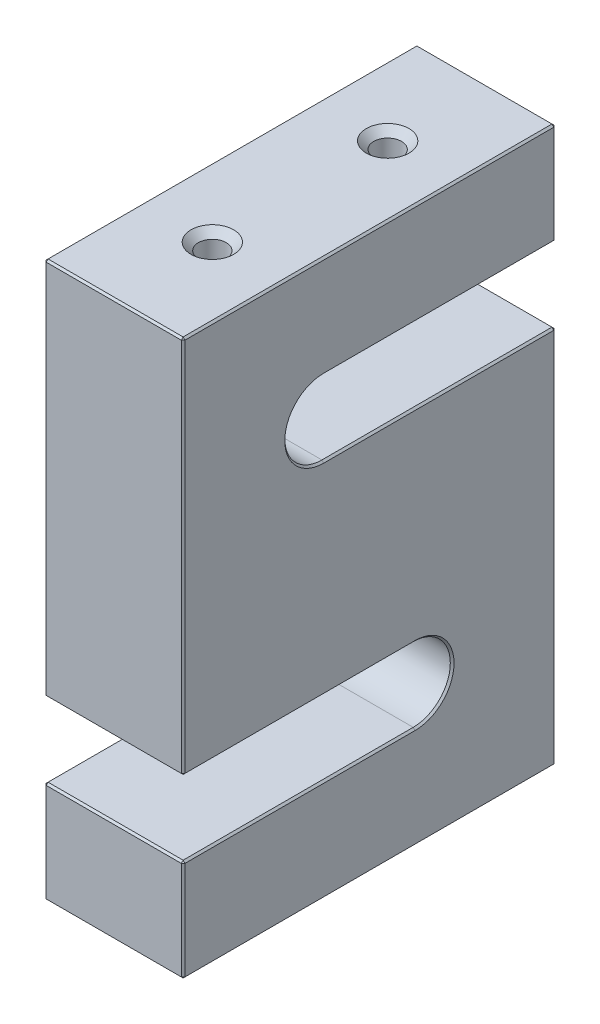
SolidWorks part; units mm, degrees
ref_plane "Front" through (0, 0, 0) normal (0, 0, 1) x (1, 0, 0)
ref_plane "Top" through (0, 0, 0) normal (0, 1, 0) x (1, 0, 0)
ref_plane "Right" through (0, 0, 0) normal (1, 0, 0) x (0, 0, -1)
sketch "Sketch1" plane through (0, 0, 0) normal (1, 0, 0) x (0, 0, -1)
  line L0 (-25.5, 0) -> (25.5, 0) construction
  line L1 (25.5, -38) -> (-25.5, -38) construction
  line L2 (25.5, -38) -> (25.5, 13.92)
  line L3 (25.5, 38) -> (-25.5, 38) construction
  line L4 (-25.5, -38) -> (-25.5, 38) construction
  line L5 (25.5, -38) -> (-25.5, 38) construction
  line L6 (25.5, 38) -> (-25.5, -38) construction
  line L7 (-25.5, 19) -> (25.5, 19) construction
  line L8 (-6.25, 19) -> (29.6244, 19) construction
  line L9 (-6.25, 24.08) -> (25.5, 24.08) construction
  line L10 (-6.25, 13.92) -> (25.5, 13.92) construction
  line L11 (6.25, -24.03) -> (-25.5, -24.03)
  line L12 (6.25, -13.87) -> (-25.5, -13.87) construction
  line L13 (11.33, -18.95) -> (-25.5, -18.95) construction
  line L14 (25.5, 38) -> (25.5, 24.08)
  line L15 (25.5, 24.08) -> (-6.25, 24.08)
  line L16 (25.5, 38) -> (-25.5, 38)
  line L17 (-25.5, 38) -> (-25.5, -13.87)
  line L18 (6.25, -13.87) -> (-25.5, -13.87)
  line L19 (25.5, 24.08) -> (25.5, 38)
  line L20 (-25.5, -24.03) -> (-25.5, -38)
  line L21 (-25.5, -38) -> (25.5, -38)
  line L23 (25.5, 13.92) -> (-6.25, 13.92)
  arc A0 (-6.25, 24.08) -> (-6.25, 13.92) centre (-6.25, 19) ccw construction
  arc A2 (6.25, -24.03) -> (6.25, -13.87) centre (6.25, -18.95) ccw construction
  arc A3 (-6.25, 24.08) -> (-6.25, 13.92) centre (-6.25, 19) ccw
  arc A4 (6.25, -13.87) -> (6.25, -24.03) centre (6.25, -18.95) cw
  point P0 (0, 0)
  point P12 (8.4372, 19)
  point P24 (0, 0.025)
  dimension "D1" = 51
  dimension "D2" = 76
  dimension "D3" = 19
  dimension "D6" = 10.16
  dimension "D7" = 19.05
  dimension "D5" = 2
extrude "Boss-Extrude1" add sketch "Sketch1" along normal blind 19 contours L18 A4 L11 L20 L21 L2 L23 A3 L15 L14 L16 L17
sketch "Sketch2" plane through (0, -38, 0) normal (0, -1, 0) x (1, 0, 0)
  line L0 (9.5, 25.5) -> (9.5, -25.5) construction
  line L1 (19, 25.5) -> (0, 25.5) construction
  line L2 (19, -25.5) -> (0, -25.5) construction
  line L3 (0, 0) -> (19, 0) construction
  line L4 (0, 25.5) -> (0, -25.5) construction
  line L5 (19, 25.5) -> (19, -25.5) construction
  circle A0 centre (9.5, 12) radius 1.905
  circle A1 centre (9.5, -12) radius 1.905
  dimension "D2" = 3.81
  dimension "D1" = 12
extrude "Cut-Extrude1" cut sketch "Sketch2" against normal blind 10.16
chamfer "Chamfer1" distance 1.016 angle 45 2 edges at (9.5, -38, 10.095) (9.5, -38, -10.095)
chamfer "Chamfer2" distance 0.254 angle 45 32 edges at (0, -38, 0) (0, 24.08, -9.625) (0, 38, 0) (0, -24.03, 9.625) (0, -18.95, -11.33) (0, -13.87, 9.625) (0, 19, 11.33) (0, 13.92, -9.625) (9.5, 24.08, -25.5) (0, 31.04, -25.5) (9.5, 38, -25.5) (9.5, -38, -25.5) (0, -12.04, -25.5) (9.5, 13.92, -25.5) (9.5, -24.03, 25.5) (0, -31.015, 25.5) (9.5, -38, 25.5) (9.5, 38, 25.5) (0, 12.065, 25.5) (9.5, -13.87, 25.5) (19, 12.065, 25.5) (19, 38, 0) (19, 31.04, -25.5) (19, 24.08, -9.625) (19, 19, 11.33) (19, 13.92, -9.625) (19, -12.04, -25.5) (19, -38, 0) (19, -31.015, 25.5) (19, -24.03, 9.625) (19, -18.95, -11.33) (19, -13.87, 9.625)
mirror "Mirror3" about plane through (0, 0, 0) normal (0, 1, 0) of "Cut-Extrude1"
chamfer "Chamfer3" distance 1.016 angle 45 2 edges at (9.5, 38, -10.095) (9.5, 38, 10.095)
